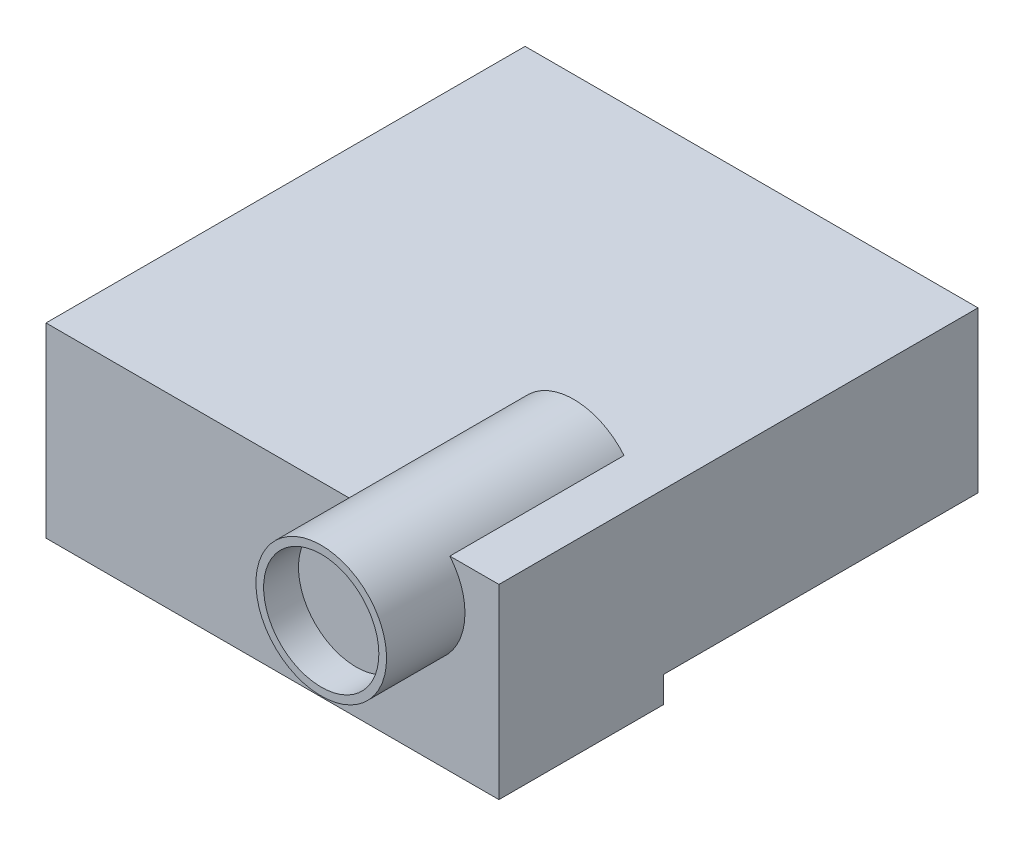
SolidWorks part; units mm, degrees
ref_plane "정면" through (0, 0, 0) normal (0, 0, 1) x (1, 0, 0)
ref_plane "윗면" through (0, 0, 0) normal (0, 1, 0) x (1, 0, 0)
ref_plane "우측면" through (0, 0, 0) normal (1, 0, 0) x (0, 0, -1)
sketch "스케치1" plane through (0, 0, 0) normal (0, 1, 0) x (1, 0, 0)
  line L1 (0, 0) -> (260, 0)
  line L2 (0, 0) -> (0, 275)
  line L3 (0, 275) -> (260, 275)
  line L4 (260, 0) -> (260, 275)
  dimension "D1" = 260
  dimension "D2" = 275
extrude "보스-돌출1" add sketch "스케치1" along normal blind 107
sketch "스케치2" plane through (0, 0, 0) normal (0, 0, 1) x (1, 0, 0)
  line L0 (260, 107) -> (260, 0) construction
  line L2 (0, 0) -> (260, 0) construction
  circle A0 centre (203, 83) radius 37.5
  dimension "D2" = 75
  dimension "D1" = 57
  dimension "D3" = 83
extrude "보스-돌출2" add sketch "스케치2" along normal blind 25 and the other way blind 100
sketch "스케치3" plane through (260, 0, 0) normal (1, 0, 0) x (0, 0, -1)
  line L0 (275, 107) -> (275, 0) construction
  line L1 (275, 15) -> (94.4841, 15)
  line L2 (275, 15) -> (275, 0)
  line L3 (275, 0) -> (94.4841, 0)
  line L4 (94.4841, 15) -> (94.4841, 0)
  line L5 (0, 0) -> (275, 0) construction
  dimension "D1" = 15
extrude "컷-돌출1" cut sketch "스케치3" against normal through all
hole_wizard "M4x0.7 나사 구멍1" positions "스케치5" profile "스케치4" tap size "M4x0.7" standard "Ansi Metric"
sketch "스케치5" plane through (0, 15, 0) normal (0, -1, 0) x (-1, 0, 0)
  line L0 (0, 235) -> (-36, 235) construction
  line L1 (0, 275) -> (0, 94.4841) construction
  line L2 (-36, 235) -> (-209, 235) construction
  line L3 (-209, 235) -> (-260, 235) construction
  line L4 (-260, 275) -> (-260, 94.4841) construction
  line L6 (0, 275) -> (-260, 275) construction
  point P0 (-36, 235)
  point P2 (-209, 235)
  dimension "D1" = 173
  dimension "D2" = 40
  dimension "D3" = 36
sketch "스케치4" plane through (36, 15, -235) normal (1, 0, 0) x (0, 0, -1)
  line L0 (0, 0) -> (0, 12.4914)
  line L1 (0, 12.4914) -> (1.65, 11.5)
  line L2 (1.65, 11.5) -> (1.65, 0)
  line L5 (1.65, 0) -> (0, 0)
  line L10 (0, 12.4914) -> (-1.65, 11.5) construction
  line L11 (0, -6.35) -> (0, 107.95) construction
  dimension "탭 드릴 지름" = 3.3
  dimension "탭 드릴 깊이" = 11.5
  dimension "드릴 각도" = 118
cosmetic thread "구멍 나사산1" parameters "D1"=8, "D2"=4
cosmetic thread "구멍 나사산2" parameters "D1"=8, "D2"=4
hole_wizard "M4x0.7 나사 구멍2" positions "스케치7" profile "스케치6" tap size "M4x0.7" standard "Ansi Metric"
sketch "스케치7" plane through (0, 0, 0) normal (0, -1, 0) x (-1, 0, 0)
  point P0 (-142, 47)
  dimension "D1" = 188
  dimension "D2" = 67
sketch "스케치6" plane through (142, 0, -47) normal (1, 0, 0) x (0, 0, -1)
  line L0 (0, 0) -> (0, 12.4914)
  line L1 (0, 12.4914) -> (1.65, 11.5)
  line L2 (1.65, 11.5) -> (1.65, 0)
  line L5 (1.65, 0) -> (0, 0)
  line L10 (0, 12.4914) -> (-1.65, 11.5) construction
  line L11 (0, -6.35) -> (0, 107.95) construction
  dimension "탭 드릴 지름" = 3.3
  dimension "탭 드릴 깊이" = 11.5
  dimension "드릴 각도" = 118
cosmetic thread "구멍 나사산3" parameters "D1"=8, "D2"=4
ref_plane "평면1" through (203, 0, 0) normal (1, 0, 0) x (0, 0, -1)
sketch "스케치17" plane through (0, 0, 25) normal (0, 0, 1) x (1, 0, 0)
  circle A0 centre (203, 83) radius 37.5
  circle A1 centre (203, 83) radius 33.0674
extrude "보스-돌출4" add sketch "스케치17" along normal blind 20
ref_plane "평면6" through (0, 0, 345) normal (0, 0, 1) x (1, 0, 0)
sketch "화면1" plane through (203, 0, 0) normal (1, 0, 0) x (0, 0, -1)
  line L0 (-25, 83) -> (-345, 110) construction
  line L1 (-25, 116.0674) -> (-25, 49.9326) construction
  line L2 (-345, 294.8553) -> (-345, -294.8553) construction
  line L3 (-345, 110) -> (-345, 250) construction
  line L4 (-345, 250) -> (-25, 83) construction
  line L5 (94.4841, 0) -> (0, 0) construction
  line L6 (-125, 135.1875) -> (-125, 91.4375) construction
  line L7 (-110.6263, 127.6862) -> (-125, 113.3125) construction
  line L8 (-125, 113.3125) -> (-145.1729, 93.1396) construction
  line L9 (-170.7516, 159.0641) -> (-125, 113.3125) construction
  line L10 (100, 107) -> (0, 107) construction
  line L11 (-121.6875, 333.3125) -> (-261.6875, 333.3125)
  line L14 (-125, 113.3125) -> (-101.1092, 89.4217) construction
  line L15 (0, 107) -> (275, 107) construction
  line L16 (-261.6875, 333.3125) -> (-170.7516, 159.0641)
  line L17 (-101.1092, 89.4217) -> (-121.6875, 333.3125)
  dimension "D1" = 110
  dimension "D2" = 140
  dimension "D3" = 100
  dimension "D4" = 45
  dimension "D5" = 135
sketch "화면2" plane through (0, 0, 345) normal (0, 0, 1) x (1, 0, 0)
  line L1 (295.5, 110) -> (110.5, 110)
  line L2 (295.5, 110) -> (295.5, 250)
  line L3 (295.5, 250) -> (110.5, 250)
  line L4 (110.5, 110) -> (110.5, 250)
  line L5 (295.5, 110) -> (110.5, 250) construction
  line L6 (295.5, 250) -> (110.5, 110) construction
  point P0 (203, 180)
  point P5 (203, 250)
  dimension "D1" = 185
  dimension "D2" = 140
sketch3d "화면3"
  line L0 (203, 83, 25) -> (295.5, 250, 345)
  line L1 (295.5, 110, 345) -> (203, 83, 25)
  line L2 (110.5, 110, 345) -> (203, 83, 25)
  line L3 (110.5, 110, 345) -> (110.5, 250, 345) construction
  line L4 (203, 83, 25) -> (110.5, 250, 345)
ref_plane "평면7" through (0, 0, 12.5) normal (0, 0, 1) x (1, 0, 0)
ref_plane "평면8" through (203, 113.3125, 125) normal (0, -0.7071, 0.7071) x (-1, 0, 0)
sketch3d "3D스케치1"
  line L0 (203, 159.0641, 170.7516) -> (245.1313, 159.0641, 170.7516)
  line L1 (203, 83, 25) -> (295.5, 250, 345) construction
  line L2 (203, 89.4217, 101.1092) -> (180.9997, 89.4217, 101.1092)
  line L3 (110.5, 110, 345) -> (203, 83, 25) construction
  line L4 (203, 89.4217, 101.1092) -> (225.0003, 89.4217, 101.1092)
  line L5 (157.9522, 159.0641, 170.7516) -> (203, 159.0641, 170.7516)
  line L6 (295.5, 110, 345) -> (203, 83, 25) construction
  line L7 (157.9522, 159.0641, 170.7516) -> (180.9997, 89.4217, 101.1092)
  line L8 (245.1313, 159.0641, 170.7516) -> (225.0003, 89.4217, 101.1092)
ref_plane "평면9" through (0, 333.3125, 0) normal (0, 1, 0) x (1, 0, 0)
sketch "스케치20" plane through (0, 333.3125, 0) normal (0, 1, 0) x (1, 0, 0)
  line L0 (203, -121.6875) -> (203, -261.6875) construction
  line L1 (110.5, -261.6875) -> (295.5, -261.6875)
  line L2 (110.5, -261.6875) -> (110.5, -121.6875)
  line L3 (110.5, -121.6875) -> (295.5, -121.6875)
  line L4 (295.5, -261.6875) -> (295.5, -121.6875)
  line L5 (110.5, -261.6875) -> (295.5, -121.6875) construction
  line L6 (110.5, -121.6875) -> (295.5, -261.6875) construction
  point P0 (203, -191.6875)
  dimension "D1" = 140
  dimension "D2" = 185
